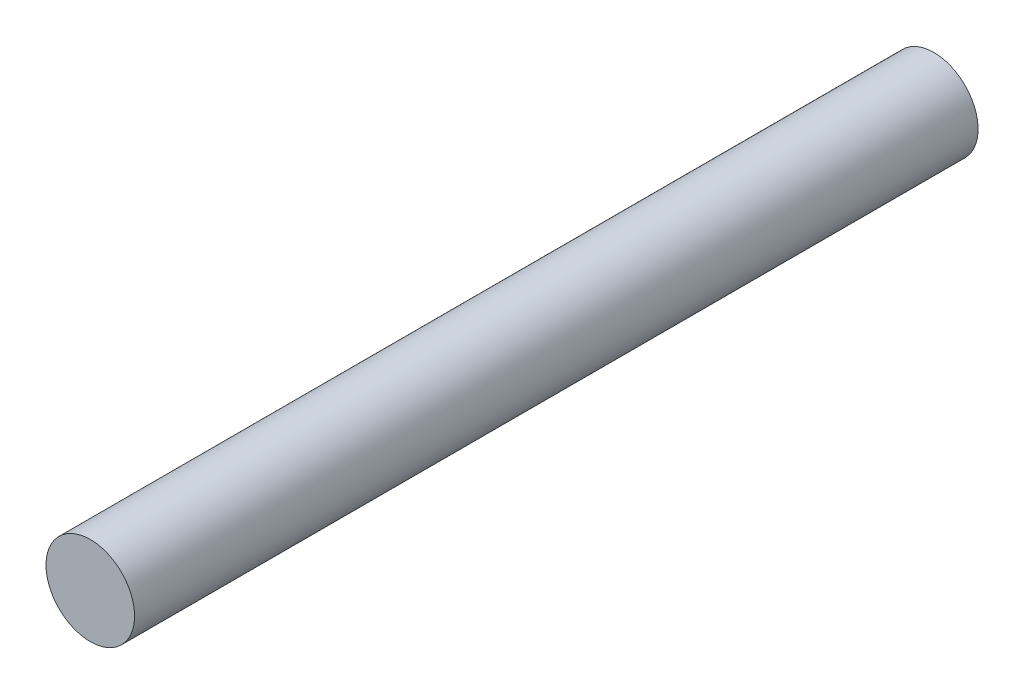
SolidWorks part; units mm, degrees
material "Plain Carbon Steel"
ref_plane "Front Plane" through (0, 0, 0) normal (0, 0, 1) x (1, 0, 0)
ref_plane "Top Plane" through (0, 0, 0) normal (0, 1, 0) x (1, 0, 0)
ref_plane "Right Plane" through (0, 0, 0) normal (1, 0, 0) x (0, 0, -1)
sketch "Sketch1" plane through (0, 0, 0) normal (0, 0, 1) x (1, 0, 0)
  circle A0 centre (0, 0) radius 4
extrude "Boss-Extrude1" add sketch "Sketch1" along normal blind 76.2
